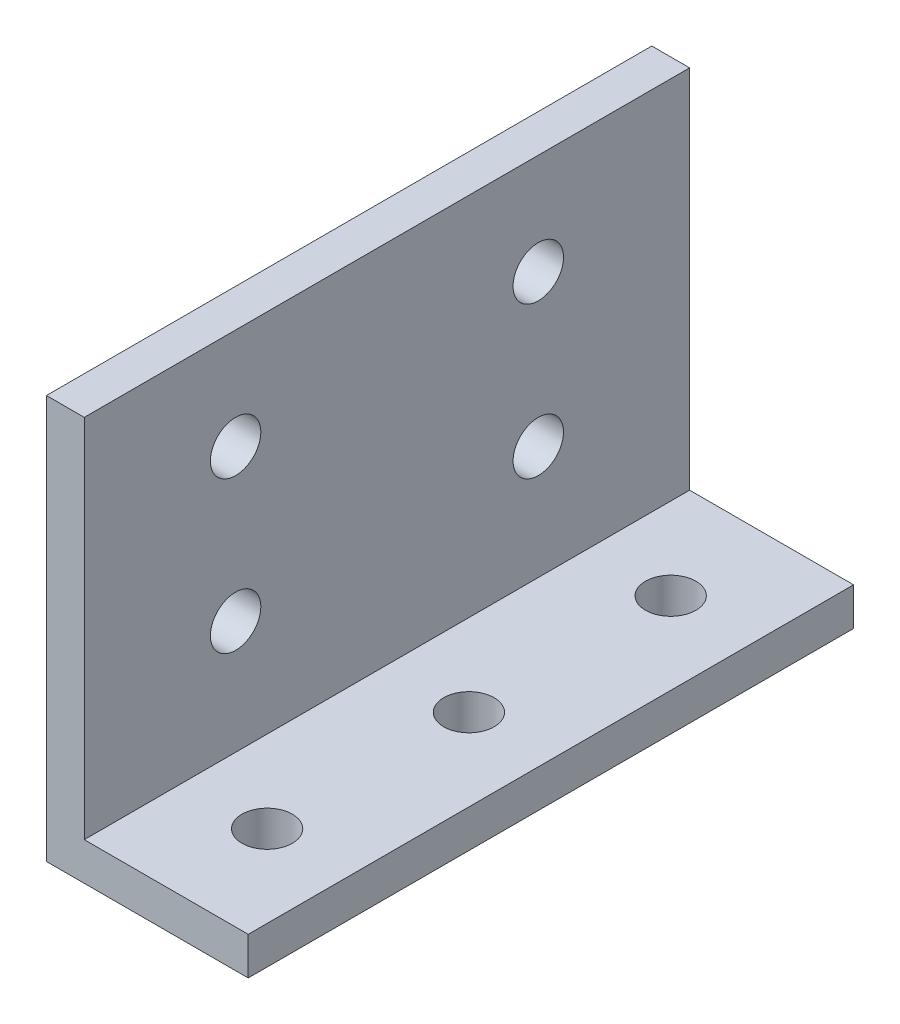
SolidWorks part; units mm, degrees
material "6061 Alloy"
ref_plane "Front Plane" through (0, 0, 0) normal (0, 0, 1) x (1, 0, 0)
ref_plane "Top Plane" through (0, 0, 0) normal (0, 1, 0) x (1, 0, 0)
ref_plane "Right Plane" through (0, 0, 0) normal (1, 0, 0) x (0, 0, -1)
sketch "Sketch1" plane through (0, 0, 0) normal (0, 0, 1) x (1, 0, 0)
  line L0 (0, 0) -> (0, 46.0375)
  line L1 (0, 0) -> (20.6375, 0)
  line L2 (-4.7625, -4.7625) -> (20.6375, -4.7625)
  line L3 (-4.7625, -4.7625) -> (-4.7625, 46.0375)
  line L4 (0, 46.0375) -> (-4.7625, 46.0375)
  line L5 (20.6375, 0) -> (20.6375, -4.7625)
  dimension "D2" = 50.8
  dimension "D3" = 25.4
  dimension "D1" = 4.7625
extrude "Boss-Extrude1" add sketch "Sketch1" along normal blind 76.2
sketch "Sketch2" plane through (0, 0, 0) normal (1, 0, 0) x (0, 0, -1)
  line L0 (-76.2, 46.0375) -> (0, 46.0375) construction
  line L1 (-76.2, 0) -> (-76.2, 46.0375) construction
  circle A0 centre (-57.15, 33.3375) radius 3.175
  circle A1 centre (-19.05, 33.3375) radius 3.175
  circle A3 centre (-19.05, 14.2875) radius 3.175
  circle A5 centre (-57.15, 14.2875) radius 3.175
  dimension "D1" = 6.35
  dimension "D2" = 12.7
  dimension "D3" = 19.05
  dimension "D4" = 2
  dimension "D5" = 2
extrude "Cut-Extrude1" cut sketch "Sketch2" against normal up to next
sketch "Sketch3" plane through (0, 0, 0) normal (0, 1, 0) x (1, 0, 0)
  line L0 (20.6375, 0) -> (0, 0) construction
  line L1 (20.6375, -76.2) -> (20.6375, 0) construction
  line L2 (20.6375, -76.2) -> (0, -76.2) construction
  circle A0 centre (10.3187, -12.7) radius 3.175
  circle A1 centre (10.3187, -63.5) radius 3.175
  circle A2 centre (10.3187, -38.1) radius 3.175
  dimension "D1" = 12.7
  dimension "D2" = 6.35
  dimension "D3" = 10.3187
  dimension "D4" = 10.3187
  dimension "D5" = 12.7
  dimension "D6" = 6.35
  dimension "D7" = 38.1
  dimension "D8" = 10.3187
extrude "Cut-Extrude2" cut sketch "Sketch3" against normal up to next
